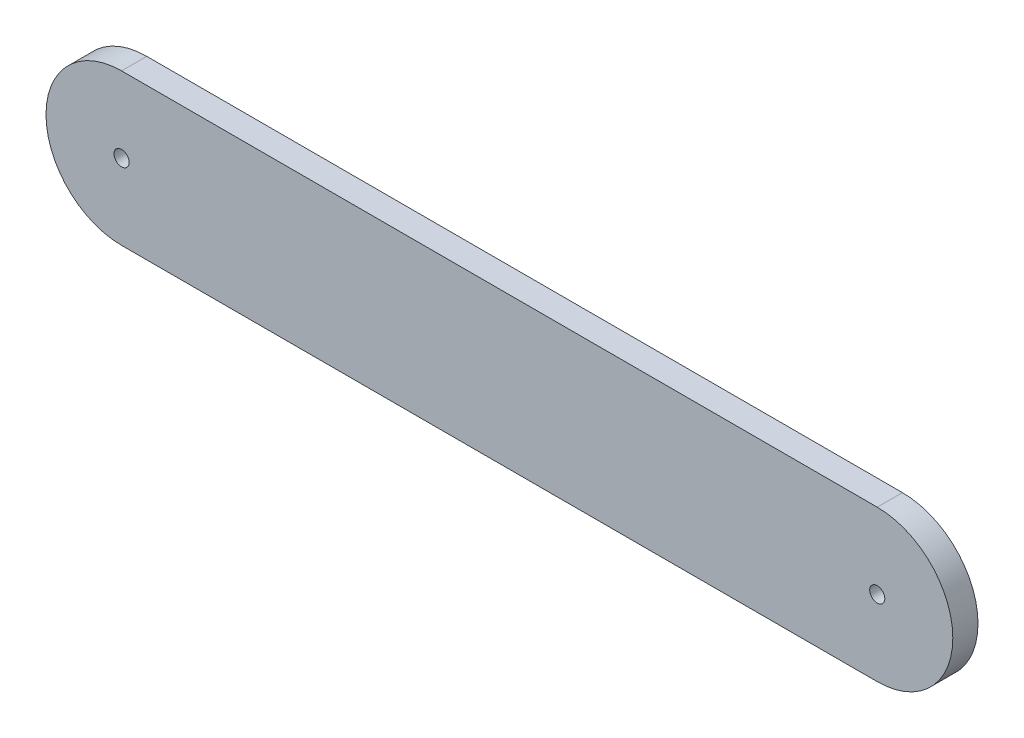
SolidWorks part; units mm, degrees
material "PVC 0.007 Plasticized"
ref_plane "Front Plane" through (0, 0, 0) normal (0, 0, 1) x (1, 0, 0)
ref_plane "Top Plane" through (0, 0, 0) normal (0, 1, 0) x (1, 0, 0)
ref_plane "Right Plane" through (0, 0, 0) normal (1, 0, 0) x (0, 0, -1)
sketch "Sketch1" plane through (0, 0, 0) normal (0, 0, 1) x (1, 0, 0)
  line L0 (-75, 0) -> (75, 0)
  dimension "D1" = 150
  dimension "D2" = 75
sketch "Sketch2" plane through (0, 0, 0) normal (0, 0, 1) x (1, 0, 0)
  line L0 (-75, 15) -> (75, 15)
  line L1 (-75, -15) -> (75, -15)
  arc A0 (-75, 15) -> (-75, -15) centre (-75, 0) ccw
  arc A1 (75, -15) -> (75, 15) centre (75, 0) ccw
  dimension "D1" = 30
  dimension "D2" = 30
extrude "Boss-Extrude1" add sketch "Sketch2" along normal blind 5
sketch "Sketch4" plane through (0, 0, 0) normal (0, 0, -1) x (-1, 0, 0)
  circle A1 centre (-75, 0) radius 1.5
  circle A3 centre (75, 0) radius 1.5
  dimension "D1" = 3
  dimension "D2" = 3
extrude "Cut-Extrude1" cut sketch "Sketch4" against normal blind 5
